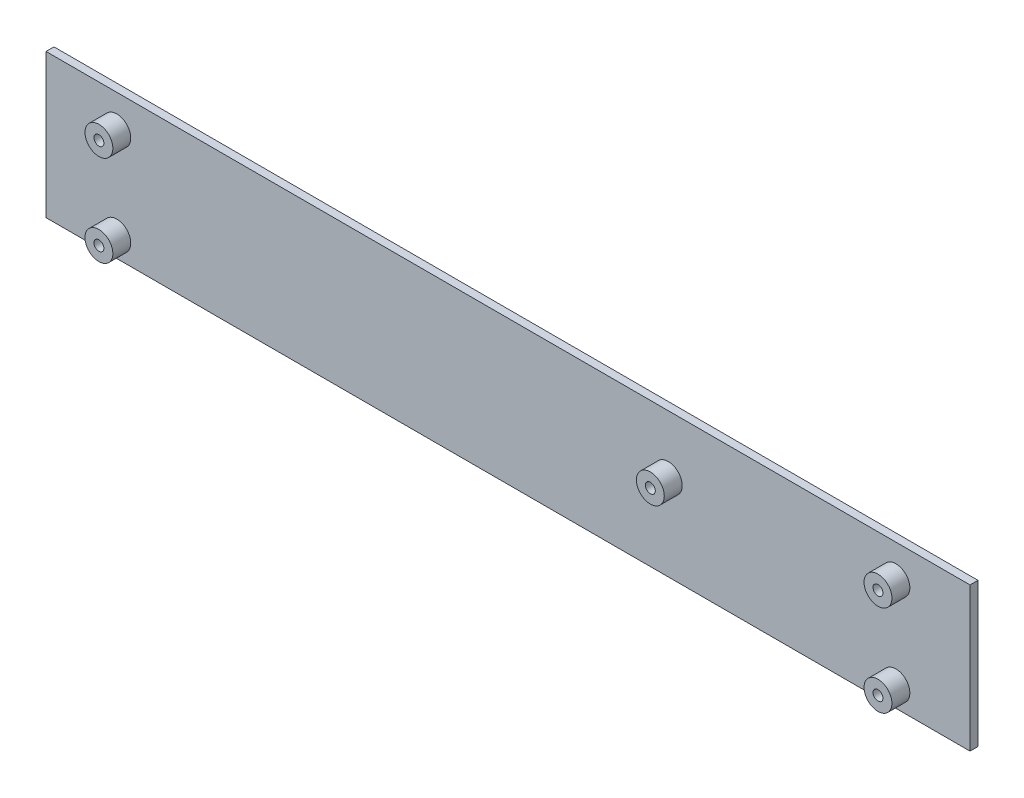
SolidWorks part; units mm, degrees
ref_plane "Front Plane" through (0, 0, 0) normal (0, 0, 1) x (1, 0, 0)
ref_plane "Top Plane" through (0, 0, 0) normal (0, 1, 0) x (1, 0, 0)
ref_plane "Right Plane" through (0, 0, 0) normal (1, 0, 0) x (0, 0, -1)
sketch "Sketch2" plane through (0, 0, -1.6) normal (0, 0, -1) x (-1, 0, 0)
  line L0 (-265.43, -73.66) -> (-276.86, -73.66) construction
  line L1 (-58.42, -73.66) -> (-290.3868, -73.66)
  line L2 (-58.42, -73.66) -> (-58.42, -37.52)
  line L3 (-58.42, -37.52) -> (-290.3868, -37.52)
  line L4 (-290.3868, -73.66) -> (-290.3868, -37.52)
  line L6 (-71.12, -40.64) -> (-71.12, -73.66) construction
  line L7 (-205.78, -37.52) -> (-154.68, -37.52) construction
  dimension "D1" = 0
  dimension "D3" = 12.7
  dimension "D4" = 0
extrude "Boss-Extrude1" add sketch "Sketch2" along normal blind 2 from offset 4.5
sketch "Sketch3" plane through (0, 0, -6.1) normal (0, 0, 1) x (1, 0, 0)
  circle A0 centre (271.78, -45.72) radius 3.5
  circle A1 centre (271.78, -68.58) radius 3.5
  circle A2 centre (214.63, -52.07) radius 3.5
  circle A3 centre (76.2, -45.72) radius 3.5
  circle A4 centre (76.2, -68.58) radius 3.5
  dimension "D1" = 7
  dimension "D2" = 7
  dimension "D3" = 7
  dimension "D4" = 7
  dimension "D5" = 7
extrude "Boss-Extrude2" add sketch "Sketch3" along normal up to surface (4.5 mm away)
hole_wizard "Tap Drill for M3x0.5 Tap1" positions "Sketch4" profile "Sketch5" hole size "M3x0.5" standard "ANSI Metric" end condition through all
sketch "Sketch4" plane through (0, 0, -1.6) normal (0, 0, 1) x (1, 0, 0)
  point P0 (271.78, -45.72)
  point P3 (271.78, -68.58)
  point P6 (214.63, -52.07)
  point P9 (76.2, -45.72)
  point P12 (76.2, -68.58)
sketch "Sketch5" plane through (271.78, -45.72, -1.6) normal (1, 0, 0) x (0, -1, 0)
  line L0 (0, 0) -> (0, 6.5)
  line L1 (0, 6.5) -> (1.25, 6.5)
  line L2 (1.25, 6.5) -> (1.25, 0)
  line L5 (1.25, 0) -> (0, 0)
  line L11 (0, -6.35) -> (0, 107.95) construction
  dimension "Thru Hole Dia." = 2.5
  dimension "Thru Hole Depth" = 6.5
